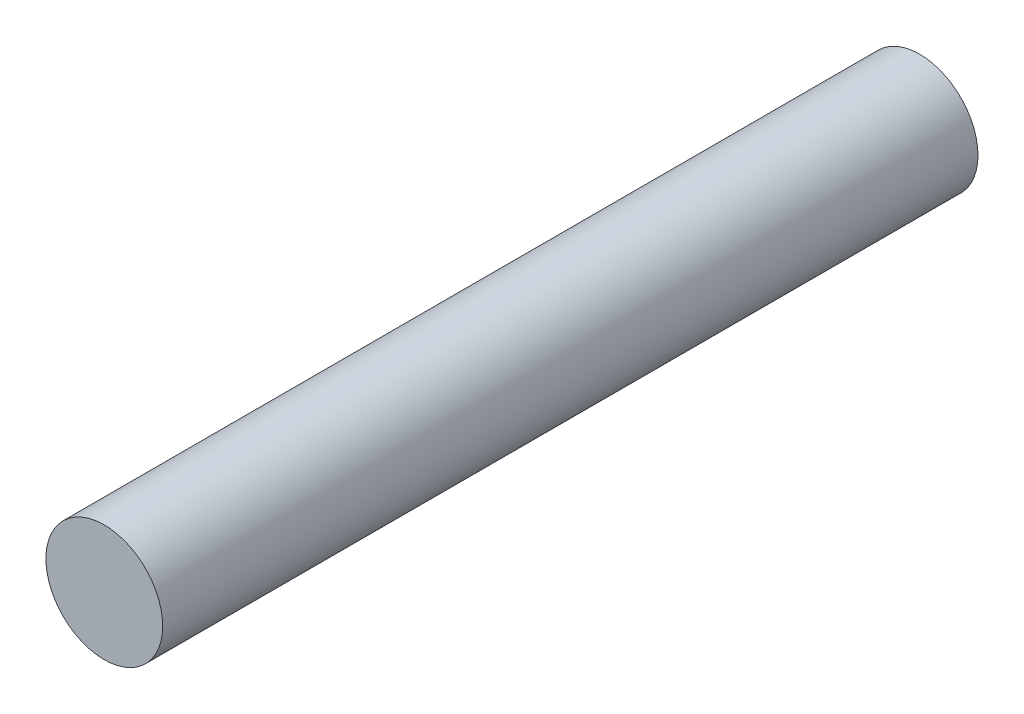
SolidWorks part; units mm, degrees
ref_plane "Front Plane" through (0, 0, 0) normal (0, 0, 1) x (1, 0, 0)
ref_plane "Top Plane" through (0, 0, 0) normal (0, 1, 0) x (1, 0, 0)
ref_plane "Right Plane" through (0, 0, 0) normal (1, 0, 0) x (0, 0, -1)
sketch "Sketch1" plane through (0, 0, 0) normal (0, 0, 1) x (1, 0, 0)
  circle A0 centre (-312.4955, -65.4669) radius 45.8248
  dimension "D1" = 91.6496
extrude "Boss-Extrude1" add sketch "Sketch1" along normal blind 640
